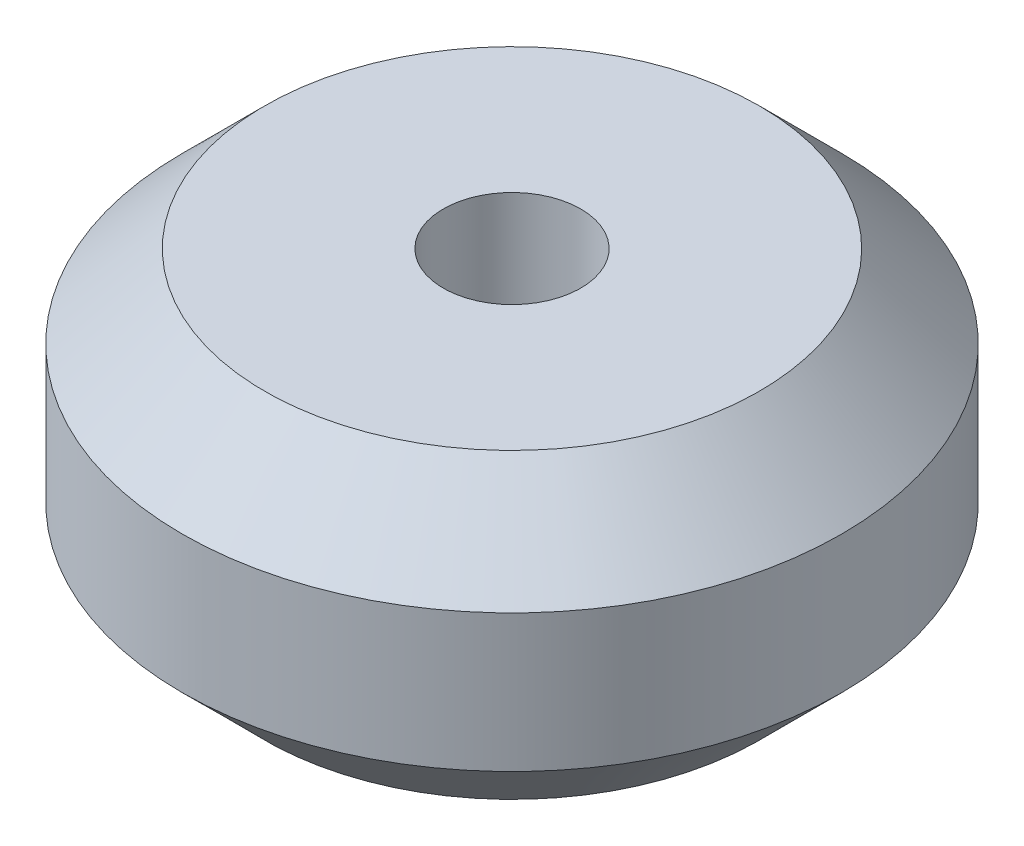
SolidWorks part; units mm, degrees
ref_plane "Front Plane" through (0, 0, 0) normal (0, 0, 1) x (1, 0, 0)
ref_plane "Top Plane" through (0, 0, 0) normal (0, 1, 0) x (1, 0, 0)
ref_plane "Right Plane" through (0, 0, 0) normal (1, 0, 0) x (0, 0, -1)
sketch "Sketch1" plane through (0, 0, 0) normal (1, 0, 0) x (0, 0, -1)
  line L0 (0, 0) -> (0, 5.5) construction
  line L1 (0, 0) -> (-12, 0) construction
  line L2 (-12, -2.5) -> (-12, 2.5)
  line L3 (-12, 2.5) -> (-9, 5.5)
  line L4 (-9, 5.5) -> (-2.5, 5.5)
  line L5 (-2.5, 5.5) -> (-2.5, -5.5)
  line L6 (-9, -5.5) -> (-2.5, -5.5)
  line L7 (-12, -2.5) -> (-9, -5.5)
  point P9 (-2.5, 0)
  point P11 (-3.8767, 5.2113)
  point P12 (-9.6688, 5.5)
  dimension "D1" = 2.5
  dimension "D2" = 12
  dimension "D3" = 11
  dimension "D4" = 45
  dimension "D5" = 5
revolve "Revolve1" add sketch "Sketch1" angle 360 about L0
